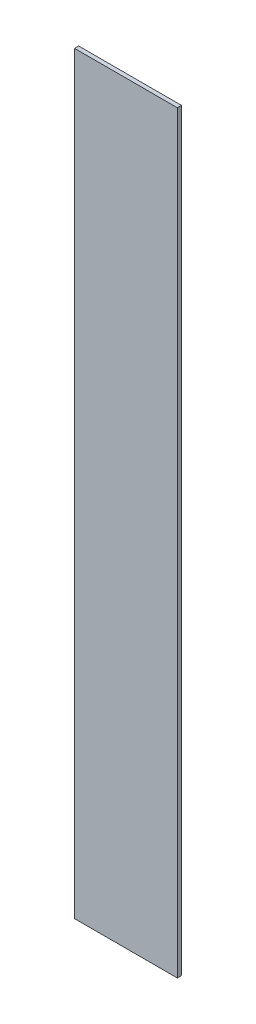
SolidWorks part; units mm, degrees
ref_plane "Plano frontal" through (0, 0, 0) normal (0, 0, 1) x (1, 0, 0)
ref_plane "Plano superior" through (0, 0, 0) normal (0, 1, 0) x (1, 0, 0)
ref_plane "Plano direito" through (0, 0, 0) normal (1, 0, 0) x (0, 0, -1)
sketch "Esboço1" plane through (0, 0, 0) normal (0, 0, 1) x (1, 0, 0)
  line L1 (-15, 110) -> (15, 110)
  line L2 (-15, 110) -> (-15, -110)
  line L3 (-15, -110) -> (15, -110)
  line L4 (15, 110) -> (15, -110)
  line L5 (-15, 110) -> (15, -110) construction
  line L6 (-15, -110) -> (15, 110) construction
  point P0 (0, 0)
  dimension "D1" = 220
  dimension "D2" = 30
extrude "Ressalto-extrusão1" add sketch "Esboço1" along normal blind 1.2
